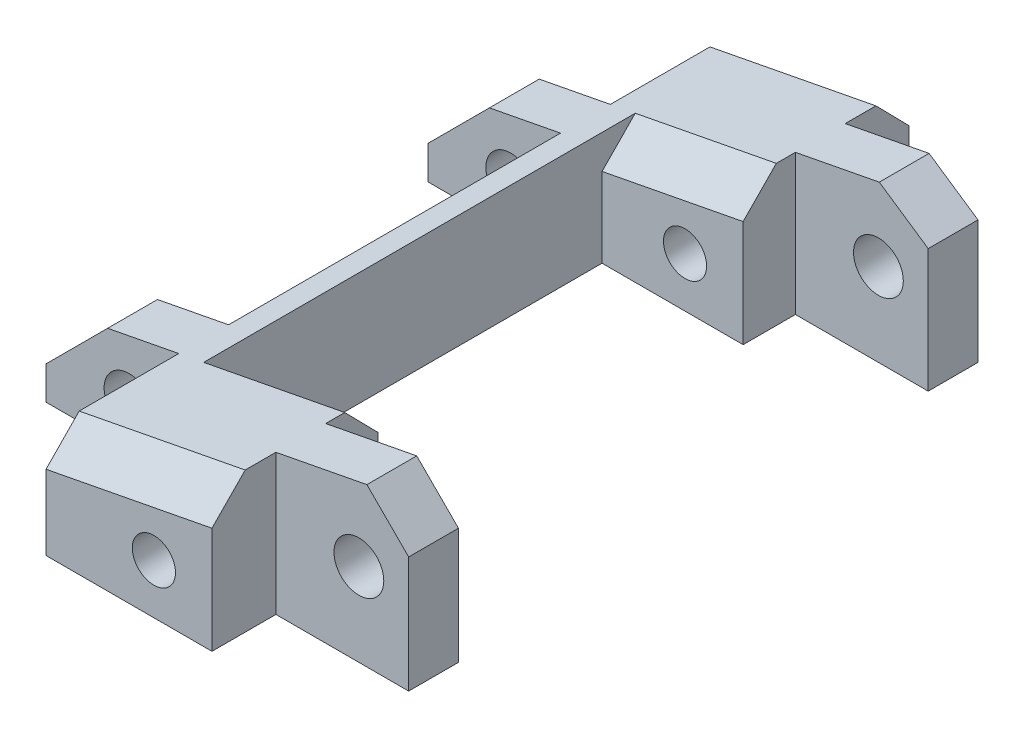
SolidWorks part; units mm, degrees
ref_plane "前视基准面" through (0, 0, 0) normal (0, 0, 1) x (1, 0, 0)
ref_plane "上视基准面" through (0, 0, 0) normal (0, 1, 0) x (1, 0, 0)
ref_plane "右视基准面" through (0, 0, 0) normal (1, 0, 0) x (0, 0, -1)
sketch "草图1" plane through (0, 0, 0) normal (0, 1, 0) x (1, 0, 0)
  line L0 (5, -17.15) -> (13, -17.15)
  line L1 (5, -21) -> (-5, -21)
  line L2 (5, -21) -> (5, -11)
  line L3 (5, 21) -> (-5, 21)
  line L4 (-5, -21) -> (-5, 21)
  line L5 (5, -21) -> (-5, 21) construction
  line L6 (5, 21) -> (-5, -21) construction
  line L7 (3.5, -11) -> (-3.5, -11)
  line L8 (-15.3944, 0) -> (11.4757, 0) construction
  line L9 (5, 11) -> (5, 21)
  line L10 (3.5, 11) -> (-3.5, 11)
  line L11 (-3.5, -11) -> (-3.5, 11)
  line L12 (3.5, -11) -> (-3.5, 11) construction
  line L13 (3.5, 11) -> (-3.5, -11) construction
  line L14 (13, -17.15) -> (13, -14.15)
  line L15 (13, -14.15) -> (5, -14.15)
  line L16 (5, 17.15) -> (13, 17.15)
  line L17 (13, 17.15) -> (13, 14.15)
  line L18 (13, 14.15) -> (5, 14.15)
  line L19 (0, 10.7263) -> (0, -12.0299) construction
  line L20 (-13, -13) -> (-13, -10)
  line L21 (-5, 13) -> (-13, 13)
  line L22 (-5, 13) -> (-5, 10)
  line L23 (-5, 10) -> (-13, 10)
  line L24 (-13, 13) -> (-13, 10)
  line L25 (-5, -10) -> (-13, -10)
  line L26 (-5, -13) -> (-5, -10)
  line L27 (-5, -13) -> (-13, -13)
  line L28 (3.5, 11) -> (5, 11)
  line L29 (3.5, -11) -> (5, -11)
  point P0 (0, 0)
  point P6 (0, 0)
  dimension "D1" = 42
  dimension "D2" = 7
  dimension "D3" = 10
  dimension "D4" = 3
  dimension "D5" = 8
  dimension "D6" = 14.15
  dimension "D7" = 3
  dimension "D8" = 8
  dimension "D9" = 10
  dimension "D10" = 10
extrude "凸台-拉伸1" add sketch "草图1" along normal blind 10
sketch "草图2" plane through (0, 0, 21) normal (0, 0, 1) x (1, 0, 0)
  line L1 (5, 0) -> (13, 0) construction
  line L2 (5, 10) -> (5, 0) construction
  line L3 (-5, 10) -> (-5, 0) construction
  line L4 (-5, 0) -> (-13, 0) construction
  line L5 (5, 0) -> (-5, 0) construction
  line L6 (-13, 5) -> (13, 10)
  line L7 (-13, 10) -> (-13, 0) construction
  line L8 (-13, 5) -> (-13, 10)
  line L9 (-13, 10) -> (13, 10)
  line L10 (5, 10) -> (5, 0) construction
  circle A0 centre (10, 5) radius 1.5
  circle A1 centre (-8, 2.5) radius 1.5
  circle A2 centre (1.5, 3) radius 1.3
  dimension "D1" = 3
  dimension "D2" = 3
  dimension "D7" = 2.6
  dimension "D3" = 5
  dimension "D4" = 5
  dimension "D5" = 3
  dimension "D6" = 2.5
  dimension "D8" = 3
  dimension "D9" = 3.5
extrude "切除-拉伸1" cut sketch "草图2" against normal through all
chamfer "倒角1" distance 3 angle 45 4 edges at (13, 10, -15.65) (13, 10, 15.65) (-13, 5, -11.5) (-13, 5, 11.5)
chamfer "倒角2" distance 2 angle 45 4 edges at (0, 7.5, -21) (0.75, 7.6442, -11) (0.75, 7.6442, 11) (0, 7.5, 21)
